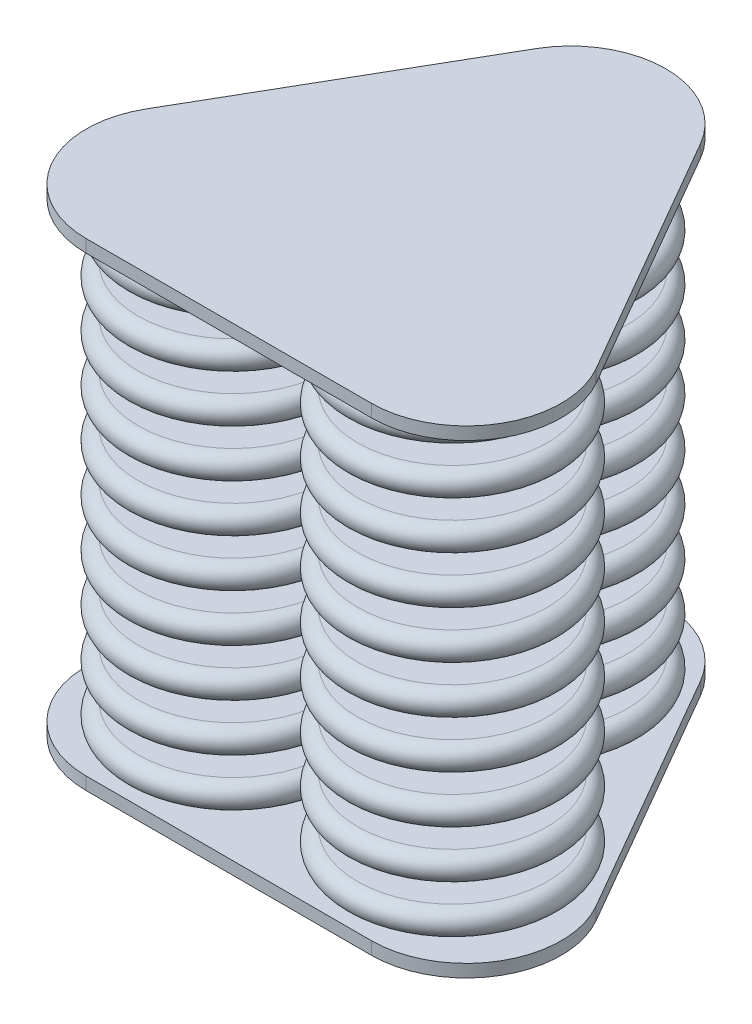
SolidWorks part; units mm, degrees
ref_plane "Front Plane" through (0, 0, 0) normal (0, 0, 1) x (1, 0, 0)
ref_plane "Top Plane" through (0, 0, 0) normal (0, 1, 0) x (1, 0, 0)
ref_plane "Right Plane" through (0, 0, 0) normal (1, 0, 0) x (0, 0, -1)
sketch "Sketch1" plane through (0, 0, 0) normal (0, 1, 0) x (1, 0, 0)
  line L0 (0, 0) -> (0, 20) construction
  circle A0 centre (0, 20) radius 5
  circle A1 centre (17.3205, -10) radius 5
  circle A2 centre (-17.3205, -10) radius 5
  point P10 (0, 0)
  dimension "D4" = 10
  dimension "D1" = 20
  dimension "D2" = 3
sketch "Sketch3" plane through (0, 0, 0) normal (1, 0, 0) x (0, 0, -1)
  line L0 (0, 0) -> (0, 70)
  dimension "D1" = 70
sweep "Sweep1" add profiles "Sketch1" path "Sketch3"
sketch "Sketch4" plane through (0, 0, 0) normal (1, 0, 0) x (0, 0, -1)
  line L0 (20, 0) -> (20, 8.1368) construction
  line L2 (20, 4) -> (35, 4)
  line L3 (35, 0) -> (20, 0)
  line L4 (20, 4) -> (20, 0)
  line L5 (15, 0) -> (25, 0) construction
  arc A0 (35, 4) -> (35, 0) centre (35, 2) cw
  point P0 (20, 0)
  point P2 (0, 0)
  dimension "D2" = 2
  dimension "D1" = 15
revolve "Revolve1" add sketch "Sketch4" angle 360 about L0
ref_plane "Plane1" through (17.32, 0, 0) normal (1, 0, 0) x (0, 0, -1)
sketch "Sketch7" plane through (17.32, 0, 0) normal (1, 0, 0) x (0, 0, -1)
  line L1 (-10, 0) -> (5, 0)
  line L2 (-10, 0) -> (-10, 4)
  line L3 (-10, 4) -> (5, 4)
  line L4 (-15, 0) -> (-5, 0) construction
  arc A0 (5, 4) -> (5, 0) centre (5, 2) cw
  point P4 (-10, 0)
  point P7 (0, 0)
  dimension "D2" = 15
  dimension "D1" = 4
revolve "Revolve2" add sketch "Sketch7" angle 360 about L2
ref_plane "Plane2" through (-17.32, 0, 0) normal (1, 0, 0) x (0, 0, -1)
sketch "Sketch8" plane through (-17.32, 0, 0) normal (1, 0, 0) x (0, 0, -1)
  line L1 (-10, 0) -> (-25, 0)
  line L2 (-10, 0) -> (-10, 4)
  line L3 (-10, 4) -> (-25, 4)
  line L4 (-25, 0) -> (5, 0) construction
  arc A0 (-25, 4) -> (-25, 0) centre (-25, 2) ccw
  point P4 (-10, 0)
  point P7 (0, 0)
  dimension "D1" = 15
  dimension "D2" = 4
revolve "Revolve3" add sketch "Sketch8" angle 360 about L2
sketch "Sketch11" [suppressed] plane through (0, 0, 0) normal (0, 1, 0) x (1, 0, 0)
  line L1 (0, -80) -> (56.2735, -80) construction
  line L2 (0, -80) -> (56.2735, -80)
  line L3 (0, 0) -> (0, -80) construction
sketch "Sketch12" plane through (0, 0, 0) normal (0, -1, 0) x (1, 0, 0)
  line L0 (0, 0) -> (0, -56) construction
  line L1 (22.5167, 28) -> (-22.5167, 28)
  line L2 (-35.507, 5.5) -> (-12.9904, -33.5)
  line L3 (12.9904, -33.5) -> (35.507, 5.5)
  circle A0 centre (0, 0) radius 28 construction
  arc A1 (12.9904, -33.5) -> (-12.9904, -33.5) centre (0, -26) cw
  arc A2 (-35.507, 5.5) -> (-22.5167, 28) centre (-22.5167, 13) cw
  arc A3 (35.507, 5.5) -> (22.5167, 28) centre (22.5167, 13) ccw
  dimension "D1" = 15
  dimension "D2" = 28
extrude "Boss-Extrude2" add sketch "Sketch12" along normal blind 2
pattern_linear "LPattern1" count 10 spacing 7.5 along (0, 1, 0) of "Revolve1", "Revolve2", "Revolve3"
sketch "Sketch13" plane through (0, 71.5, 0) normal (0, 1, 0) x (1, 0, 0)
  line L0 (0, 0) -> (0, 56) construction
  line L1 (-12.9904, 33.5) -> (-35.507, -5.5)
  line L2 (-22.5167, -28) -> (22.5167, -28)
  line L3 (35.507, -5.5) -> (12.9904, 33.5)
  line L4 (12.9904, 33.5) -> (35.507, -5.5) construction
  circle A0 centre (0, 0) radius 28 construction
  arc A1 (12.9904, 33.5) -> (-12.9904, 33.5) centre (0, 26) ccw
  arc A2 (-35.507, -5.5) -> (-22.5167, -28) centre (-22.5167, -13) ccw
  arc A3 (22.5167, -28) -> (35.507, -5.5) centre (22.5167, -13) ccw
  dimension "D1" = 15
  dimension "D2" = 15
extrude "Boss-Extrude3" add sketch "Sketch13" along normal blind 2
